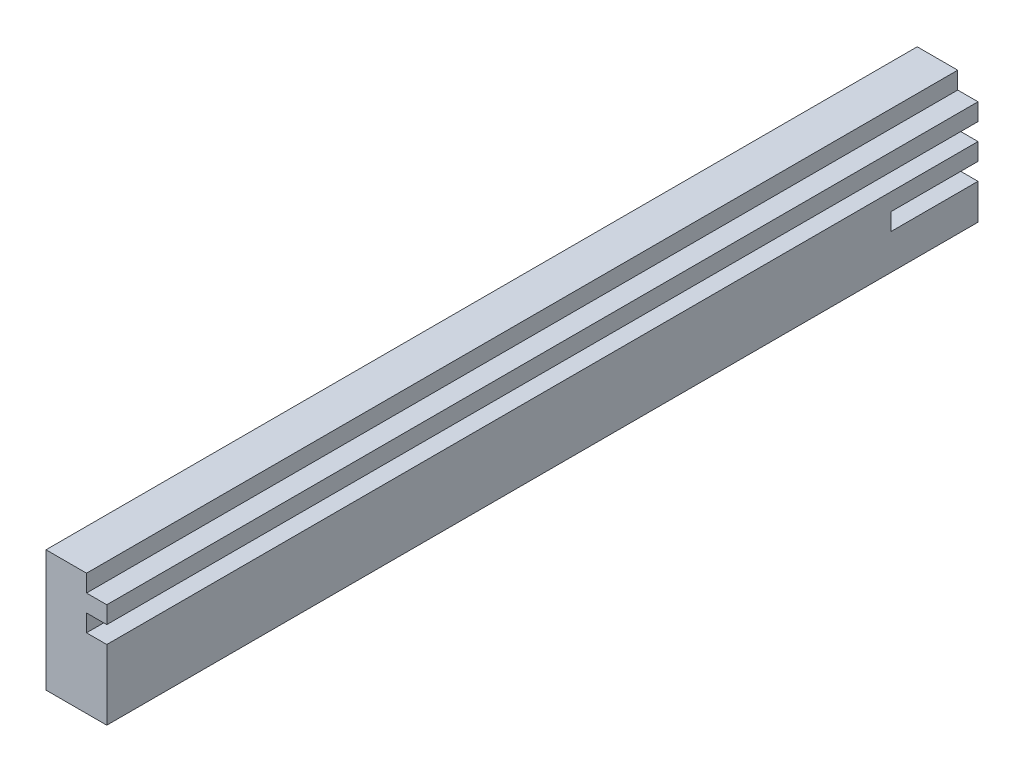
SolidWorks part; units mm, degrees
ref_plane "Front Plane" through (0, 0, 0) normal (0, 0, 1) x (1, 0, 0)
ref_plane "Top Plane" through (0, 0, 0) normal (0, 1, 0) x (1, 0, 0)
ref_plane "Right Plane" through (0, 0, 0) normal (1, 0, 0) x (0, 0, -1)
sketch "Sketch1" plane through (0, 0, 0) normal (1, 0, 0) x (0, 0, -1)
  line L1 (0, 0) -> (430, 0)
  line L2 (0, 0) -> (0, 60)
  line L3 (0, 60) -> (430, 60)
  line L4 (430, 0) -> (430, 60)
  dimension "D1" = 60
  dimension "D2" = 430
extrude "Boss-Extrude1" add sketch "Sketch1" along normal blind 30
sketch "Sketch2" plane through (30, 0, 0) normal (1, 0, 0) x (0, 0, -1)
  line L0 (430, 0) -> (430, 60) construction
  line L1 (0, 60) -> (430, 60)
  line L2 (0, 60) -> (0, 51.5)
  line L3 (0, 51.5) -> (430, 51.5)
  line L4 (430, 60) -> (430, 51.5)
  line L5 (0, 60) -> (0, 0) construction
  line L6 (0, 43) -> (430, 43)
  line L7 (0, 43) -> (0, 34.5)
  line L8 (0, 34.5) -> (430, 34.5)
  line L9 (430, 43) -> (430, 34.5)
  line L11 (430, 26) -> (387.1115, 26)
  line L12 (430, 26) -> (430, 17.5)
  line L13 (430, 17.5) -> (387.1115, 17.5)
  line L14 (387.1115, 26) -> (387.1115, 17.5)
  dimension "D1" = 8.5
  dimension "D2" = 8.5
  dimension "D3" = 8.5
  dimension "D4" = 8.5
  dimension "D5" = 8.5
extrude "Cut-Extrude1" cut sketch "Sketch2" against normal blind 10 contours L2 L1 L4 L3 | L7 L6 L9 L8 | L12 L11 L14 L13
